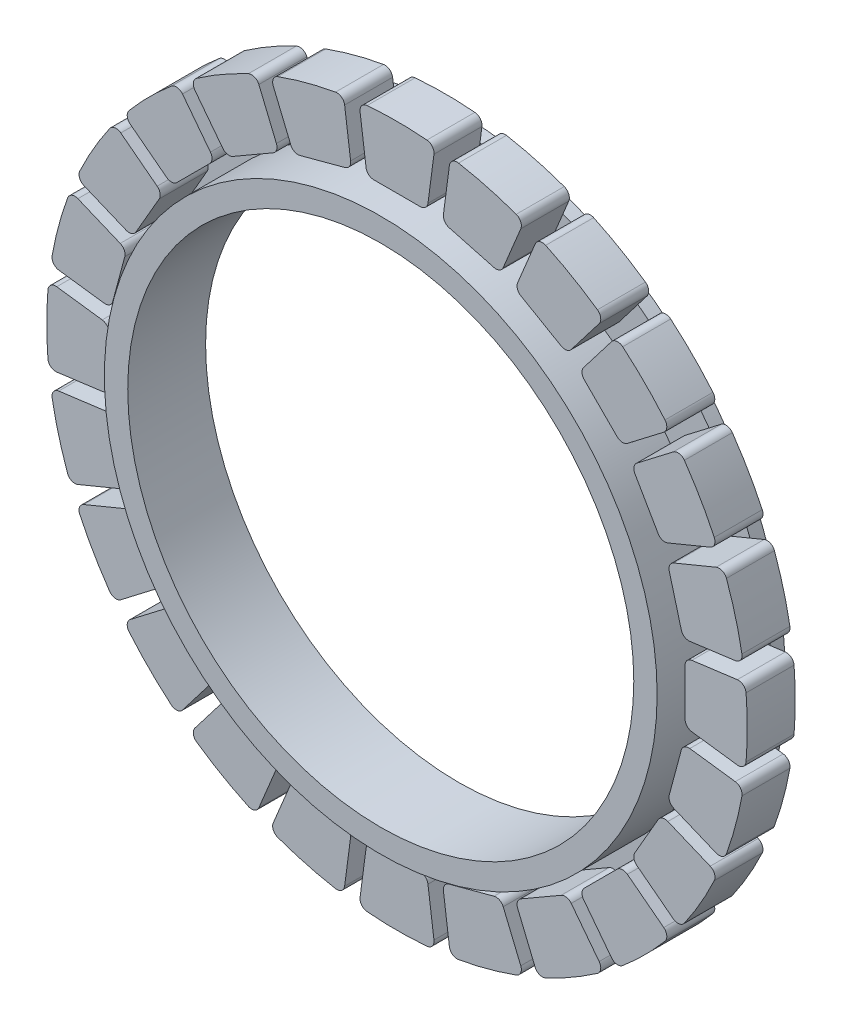
SolidWorks part; units mm, degrees
material "6061-T6 (SS)"
ref_plane "Front Plane" through (0, 0, 0) normal (0, 0, 1) x (1, 0, 0)
ref_plane "Top Plane" through (0, 0, 0) normal (0, 1, 0) x (1, 0, 0)
ref_plane "Right Plane" through (0, 0, 0) normal (1, 0, 0) x (0, 0, -1)
sketch "Sketch1" plane through (0, 0, 0) normal (0, 0, 1) x (1, 0, 0)
  line L0 (-8.9782, 83.5188) -> (-7.725, 74)
  line L1 (8.9782, 83.5188) -> (7.725, 74)
  line L2 (8.9782, 83.5188) -> (9.7616, 89.4691)
  line L3 (-8.9782, 83.5188) -> (-9.7616, 89.4691)
  line L4 (7.725, 74) -> (-7.725, 74) construction
  line L5 (0, 0) -> (-10.9642, 83.2814) construction
  line L6 (0, 0) -> (10.9642, 83.2814) construction
  line L7 (10.9642, 83.2814) -> (-10.9642, 83.2814) construction
  line L8 (0, 83.2814) -> (0, 0) construction
  line L9 (8.4842, 64.4439) -> (9.7114, 73.7656)
  line L10 (-8.4842, 64.4439) -> (-9.7114, 73.7656)
  circle A0 centre (0, 0) radius 84 construction
  arc A1 (-9.7616, 89.4691) -> (9.7616, 89.4691) centre (0, 0) cw
  circle A2 centre (0, 0) radius 90 construction
  arc A3 (-8.4842, 64.4439) -> (8.4842, 64.4439) centre (0, 0) cw
  arc A4 (7.725, 74) -> (9.7114, 73.7656) centre (0, 0) cw
  arc A5 (-7.725, 74) -> (-9.7114, 73.7656) centre (0, 0) ccw
  arc A6 (-9.2674, 70.3926) -> (9.2674, 70.3926) centre (0, 0) cw construction
  point P14 (0, 90)
  dimension "D6" = 65
  dimension "D1" = 15
  dimension "D2" = 4
  dimension "D3" = 16
  dimension "D4" = 19.5231
  dimension "D5" = 6
extrude "Boss-Extrude1" add sketch "Sketch1" along normal up to surface (20 mm away)
sketch "Sketch2" plane through (0, 0, 0) normal (0, 0, -1) x (-1, 0, 0)
  line L0 (-9.7616, 89.4691) -> (-8.9782, 83.5188)
  line L1 (9.7616, 89.4691) -> (8.9782, 83.5188)
  line L2 (9.7616, 89.4691) -> (7.725, 74) construction
  line L3 (-7.725, 74) -> (-9.7616, 89.4691) construction
  arc A0 (9.7616, 89.4691) -> (-9.7616, 89.4691) centre (0, 0) ccw construction
  arc A1 (9.7616, 89.4691) -> (-9.7616, 89.4691) centre (0, 0) ccw
  circle A2 centre (0, 0) radius 84 construction
  arc A3 (8.9782, 83.5188) -> (-8.9782, 83.5188) centre (0, 0) ccw
extrude "Cut-Extrude1" cut sketch "Sketch2" against normal up to surface (3.5 mm away)
sketch "Sketch3" plane through (0, 0, 20) normal (0, 0, 1) x (1, 0, 0)
  line L0 (7.725, 74) -> (-7.725, 74) construction
  line L1 (7.725, 74) -> (-7.725, 74)
  line L2 (9.2674, 70.3926) -> (9.7114, 73.7656)
  line L3 (-9.2674, 70.3926) -> (-9.7114, 73.7656)
  arc A0 (9.2674, 70.3926) -> (-9.2674, 70.3926) centre (0, 0) ccw construction
  arc A1 (9.2674, 70.3926) -> (-9.2674, 70.3926) centre (0, 0) ccw
  arc A2 (-7.725, 74) -> (-9.7114, 73.7656) centre (0, 0) ccw construction
  arc A3 (9.7114, 73.7656) -> (7.725, 74) centre (0, 0) ccw construction
  arc A4 (-7.725, 74) -> (-9.7114, 73.7656) centre (0, 0) ccw
  arc A5 (9.7114, 73.7656) -> (7.725, 74) centre (0, 0) ccw
extrude "Cut-Extrude2" cut sketch "Sketch3" against normal up to surface (16.5 mm away)
sketch "Sketch4" plane through (0, 0, 20) normal (0, 0, 1) x (1, 0, 0)
  line L3 (-7.725, 74) -> (7.725, 74)
  line L4 (7.725, 74) -> (9.7616, 89.4691)
  line L5 (-9.7616, 89.4691) -> (-7.725, 74)
  line L6 (-7.725, 74) -> (7.725, 74)
  line L7 (7.725, 74) -> (9.7616, 89.4691)
  line L8 (-9.7616, 89.4691) -> (-7.725, 74)
  arc A1 (9.7616, 89.4691) -> (-9.7616, 89.4691) centre (0, 0) ccw
  arc A2 (9.7616, 89.4691) -> (-9.7616, 89.4691) centre (0, 0) ccw
  dimension "D1" = 0
extrude "Cut-Extrude3" cut sketch "Sketch4" against normal offset from surface (4.175 mm away) 4.175
sketch "Sketch5" plane through (0, 0, 3.5) normal (0, 0, 1) x (1, 0, 0)
  line L0 (9.7114, 73.7656) -> (10.9642, 83.2814)
  line L1 (-9.7114, 73.7656) -> (-10.9642, 83.2814)
  line L2 (-7.725, 74) -> (-8.9782, 83.5188)
  line L3 (7.725, 74) -> (8.9782, 83.5188)
  line L4 (9.7616, 89.4691) -> (7.725, 74) construction
  line L5 (9.7114, 73.7656) -> (9.2674, 70.3926) construction
  line L6 (-7.725, 74) -> (-9.7616, 89.4691) construction
  line L7 (-9.2674, 70.3926) -> (-9.7114, 73.7656) construction
  circle A0 centre (0, 0) radius 84 construction
  arc A1 (10.9642, 83.2814) -> (8.9782, 83.5188) centre (0, 0) ccw
  arc A2 (-8.9782, 83.5188) -> (-10.9642, 83.2814) centre (0, 0) ccw
  arc A3 (9.7114, 73.7656) -> (7.725, 74) centre (0, 0) ccw construction
  arc A4 (9.7114, 73.7656) -> (7.725, 74) centre (0, 0) ccw
  arc A5 (-7.725, 74) -> (-9.7114, 73.7656) centre (0, 0) ccw construction
  arc A6 (-7.725, 74) -> (-9.7114, 73.7656) centre (0, 0) ccw
extrude "Boss-Extrude2" add sketch "Sketch5" against normal up to surface (3.5 mm away) up to face at (0, 74.0634, 0)
fillet "Fillet1" radius 2 4 edges at (-9.7616, 89.4691, 9.6625) (9.7616, 89.4691, 9.6625) (-7.725, 74, 9.6625) (7.725, 74, 9.6625)
pattern_circular "CirPattern1" count 24 over 360 about axis through (0, 0, 0) along (0, 0, 1) of "Boss-Extrude1", "Cut-Extrude1", "Cut-Extrude2", "Cut-Extrude3", "Boss-Extrude2", "Fillet1"
equation "\"num_poles\"= 24"
equation "\"D1@Sketch1\"=360/\"num_poles\""
equation "\"D1@CirPattern1\"=\"num_poles\""
